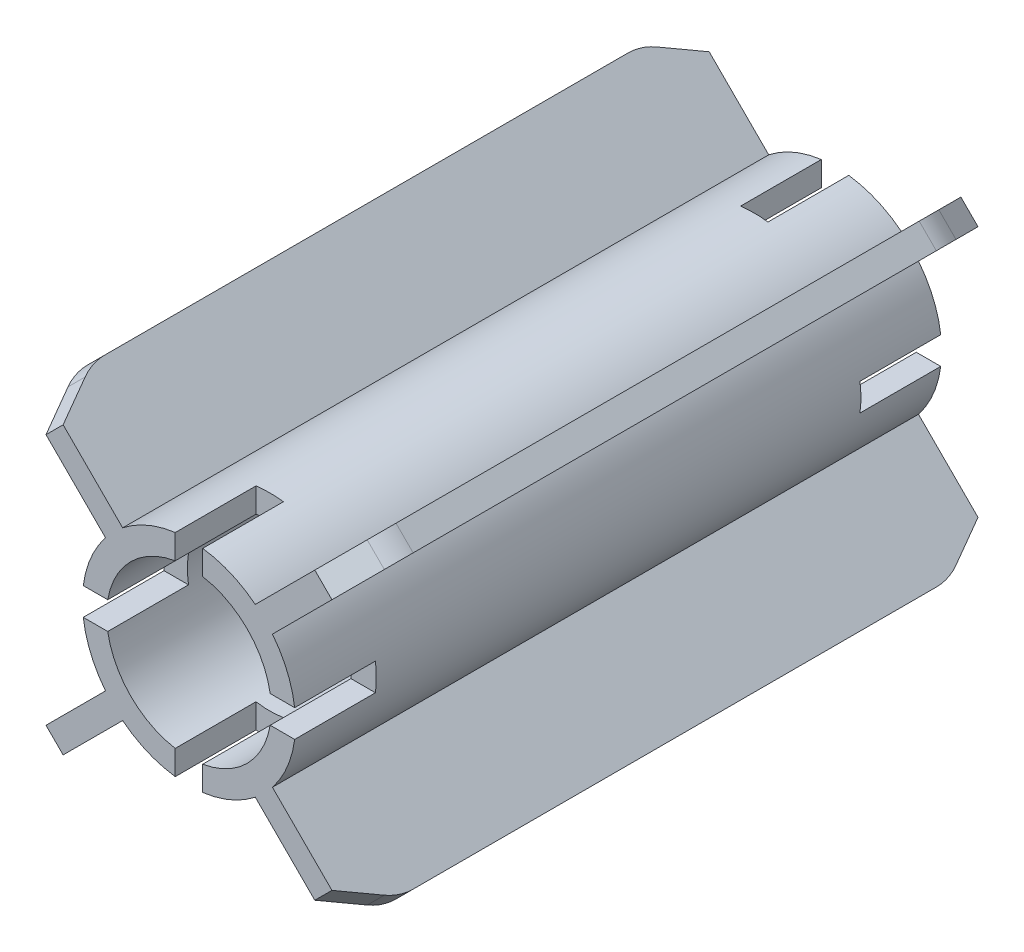
SolidWorks part; units mm, degrees
ref_plane "Front Plane" through (0, 0, 0) normal (0, 0, 1) x (1, 0, 0)
ref_plane "Top Plane" through (0, 0, 0) normal (0, 1, 0) x (1, 0, 0)
ref_plane "Right Plane" through (0, 0, 0) normal (1, 0, 0) x (0, 0, -1)
sketch "Sketch1" plane through (0, 0, 0) normal (0, 0, 1) x (1, 0, 0)
  circle A0 centre (0, 0) radius 13.2
  circle A1 centre (0, 0) radius 10.2
  dimension "D1" = 26.4
  dimension "D2" = 20.4
extrude "Boss-Extrude1" add sketch "Sketch1" along normal blind 80
sketch "Sketch2" plane through (0, 0, 80) normal (0, 0, 1) x (1, 0, 0)
  line L1 (-1.7, 10.0573) -> (1.7, 10.0573)
  line L2 (-1.7, 10.0573) -> (-1.7, 13.2)
  line L3 (-1.7, 13.2) -> (1.7, 13.2)
  line L4 (1.7, 10.0573) -> (1.7, 13.2)
  circle A0 centre (0, 0) radius 10.2 construction
  circle A1 centre (0, 0) radius 13.2 construction
  dimension "D1" = 3.4
extrude "Cut-Extrude1" cut sketch "Sketch2" against normal blind 10
pattern_circular "CirPattern1" count 4 over 360 about axis through (0, 0, 0) along (0, 0, 1) of "Cut-Extrude1"
ref_plane "Plane1" through (0, 0, 40) normal (0, 0, 1) x (1, 0, 0)
mirror "Mirror1" about plane through (0, 0, 40) normal (0, 0, 1) of "CirPattern1", "Cut-Extrude1"
ref_plane "Plane2" through (0, 0, 0) normal (0.7071, -0.7071, 0) x (-0.7071, -0.7071, 0)
sketch "Sketch5" plane through (0, 0, 0) normal (0.7071, -0.7071, 0) x (-0.7071, -0.7071, 0)
  line L0 (11.2, 0) -> (13.2, 0)
  line L1 (13.2, 0) -> (10.4582, 0) construction
  line L2 (13.2, 0) -> (23.5359, 0)
  line L3 (27, -6) -> (27, -74)
  line L4 (23.5359, -80) -> (13.2, -80)
  line L5 (13.2, -80) -> (11.2, -80)
  line L6 (10.4582, -80) -> (13.2, -80) construction
  line L7 (11.2, -80) -> (11.2, 0)
  line L8 (23.5359, -80) -> (27, -74)
  line L9 (23.5359, 0) -> (27, -6)
  dimension "D3" = 120
  dimension "D1" = 27
  dimension "D2" = 2
  dimension "D4" = 6
  dimension "D5" = 120
  dimension "D6" = 6
extrude "Boss-Extrude3" add sketch "Sketch5" along normal mid plane 3
fillet "Fillet1" radius 6 2 edges at (-19.0919, -19.0919, 74) (-19.0919, -19.0919, 6)
pattern_circular "CirPattern2" count 4 over 360 about axis through (0, 0, 0) along (0, 0, 1) of "Boss-Extrude3", "Fillet1"
equation "\"D1@Sketch1\"=\"D2@Sketch1\"+6"
